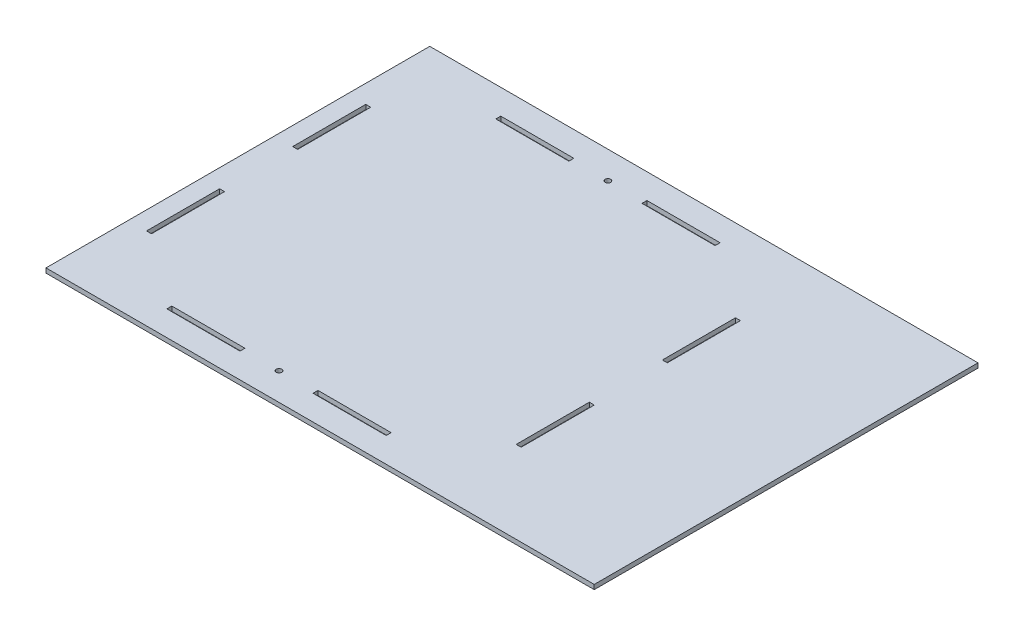
SolidWorks part; units mm, degrees
material "Oak"
ref_plane "Front Plane" through (0, 0, 0) normal (0, 0, 1) x (1, 0, 0)
ref_plane "Top Plane" through (0, 0, 0) normal (0, 1, 0) x (1, 0, 0)
ref_plane "Right Plane" through (0, 0, 0) normal (1, 0, 0) x (0, 0, -1)
sketch "Sketch1" plane through (0, 0, 0) normal (0, 1, 0) x (1, 0, 0)
  line L1 (-150, 105) -> (150, 105)
  line L2 (-150, 105) -> (-150, -105)
  line L3 (-150, -105) -> (150, -105)
  line L4 (150, 105) -> (150, -105)
  line L5 (-150, 105) -> (150, -105) construction
  line L6 (-150, -105) -> (150, 105) construction
  point P0 (0, 0)
  dimension "D1" = 300
  dimension "D2" = 210
extrude "Boss-Extrude1" add sketch "Sketch1" along normal blind 2.5
sketch "Sketch4" plane through (0, 2.5, 0) normal (0, 1, 0) x (1, 0, 0)
  line L0 (-140, 60) -> (-140, 20)
  line L1 (-140, 100) -> (65, 100)
  line L2 (-140, 100) -> (-140, -100)
  line L3 (-140, -100) -> (65, -100)
  line L4 (65, 100) -> (65, -100)
  line L5 (-150, 105) -> (-150, -105) construction
  line L6 (150, 105) -> (-150, 105) construction
  line L7 (-140, 60) -> (-137.3, 60)
  line L8 (-140, 100) -> (-137.3, 100)
  line L9 (-140, 100) -> (-140, 60)
  line L10 (-140, 60) -> (-137.3, 60)
  line L12 (-137.3, 60) -> (-137.3, 20)
  line L13 (-140, 20) -> (-137.3, 20)
  line L14 (-140, 20) -> (-140, -20)
  line L15 (-140, 20) -> (-137.3, 20)
  line L17 (-140, -20) -> (-137.3, -20)
  line L18 (-140, -20) -> (-140, -60)
  line L19 (-140, -20) -> (-137.3, -20)
  line L20 (-137.3, -20) -> (-137.3, -60)
  line L21 (-140, -60) -> (-137.3, -60)
  line L22 (-140, -60) -> (-140, -100)
  line L23 (-140, -60) -> (-137.3, -60)
  line L25 (-140, -100) -> (-137.3, -100)
  line L26 (-37.5, -100) -> (-37.5, -131.4629)
  line L27 (65, -20) -> (62.3, -20)
  line L28 (62.3, -20) -> (62.3, -60)
  line L29 (65, -60) -> (62.3, -60)
  line L30 (65, -20) -> (65, -60)
  line L31 (65, 60) -> (62.3, 60)
  line L32 (62.3, 60) -> (62.3, 20)
  line L33 (65, 20) -> (62.3, 20)
  line L34 (65, 60) -> (65, 20)
  line L35 (-97.5, 91.35) -> (-97.5, 88.65)
  line L43 (-97.5, 91.35) -> (-97.5, 88.65)
  line L44 (-97.5, 91.35) -> (-57.5, 91.35)
  line L45 (-57.5, 91.35) -> (-57.5, 88.65)
  line L46 (-97.5, 88.65) -> (-57.5, 88.65)
  line L47 (-57.5, 91.35) -> (-57.5, 88.65)
  line L49 (-17.5, 91.35) -> (-17.5, 88.65)
  line L51 (-17.5, 91.35) -> (-17.5, 88.65)
  line L52 (-17.5, 91.35) -> (22.5, 91.35)
  line L53 (22.5, 91.35) -> (22.5, 88.65)
  line L54 (-17.5, 88.65) -> (22.5, 88.65)
  line L55 (22.5, 91.35) -> (22.5, 88.65)
  line L59 (62.5, 91.35) -> (62.5, 88.65) [skipped]
  line L60 (-140, 0) -> (-181.141, 0)
  line L61 (-17.5, -91.35) -> (22.5, -91.35)
  line L62 (22.5, -91.35) -> (22.5, -88.65)
  line L63 (-17.5, -88.65) -> (22.5, -88.65)
  line L64 (-17.5, -91.35) -> (-17.5, -88.65)
  line L65 (-97.5, -91.35) -> (-57.5, -91.35)
  line L66 (-57.5, -91.35) -> (-57.5, -88.65)
  line L67 (-97.5, -88.65) -> (-57.5, -88.65)
  line L68 (-97.5, -91.35) -> (-97.5, -88.65)
  circle A0 centre (-37.5, 90) radius 1.5
  circle A1 centre (-37.5, -90) radius 1.5
  point P0 (0, 0)
  dimension "D8" = 3
  dimension "D1" = 200
  dimension "D2" = 205
  dimension "D3" = 10
  dimension "D4" = 5
  dimension "D5" = 40
  dimension "D6" = 2.7
  dimension "D9" = 2.7
  dimension "D10" = 20
  dimension "D7" = 5
  dimension "D12" = 5
extrude "Cut-Extrude1" cut sketch "Sketch4" against normal blind 2.5 contours L0 L13 L12 L7 | L2 L21 L20 L17 | L68 L65 L66 L67 | A1 | L64 L61 L62 L63 | L33 L4 L31 L32 | L29 L4 L27 L28 | A0 | L44 L45 L46 L35 | L52 L53 L54 L51
